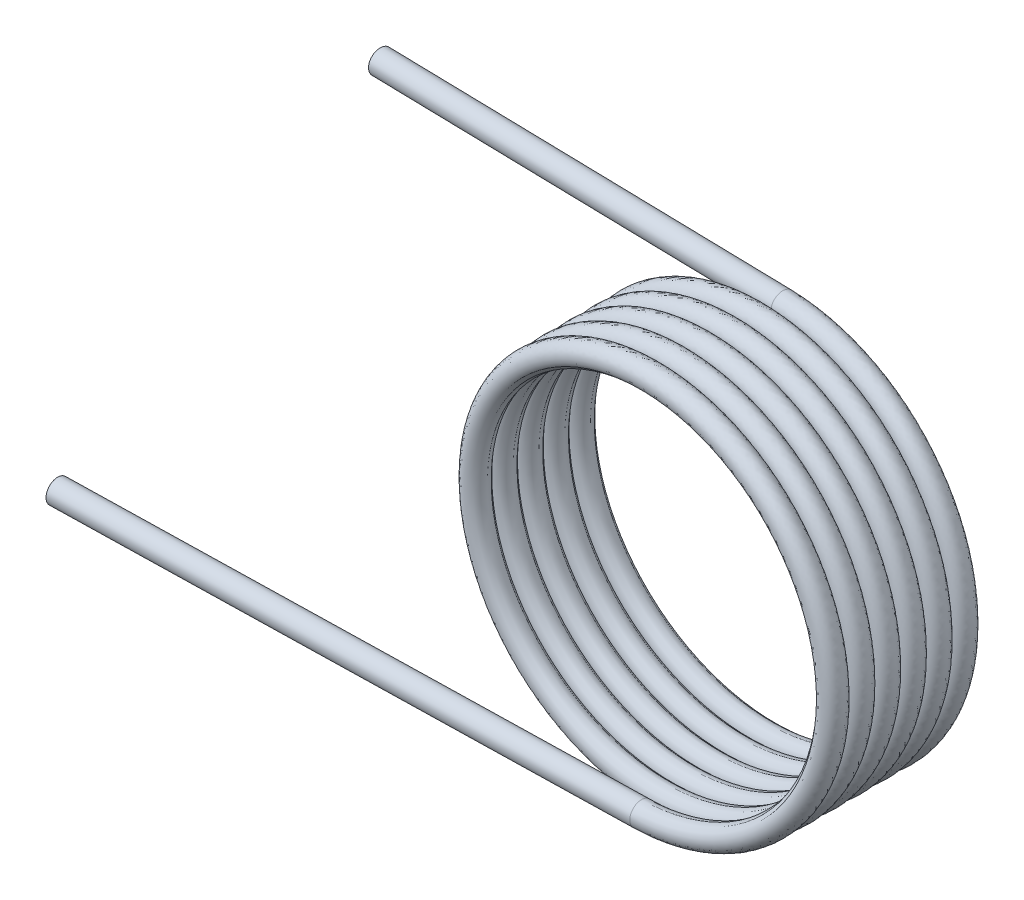
SolidWorks part; units mm, degrees
ref_plane "Front Plane" through (0, 0, 0) normal (0, 0, 1) x (1, 0, 0)
ref_plane "Top Plane" through (0, 0, 0) normal (0, 1, 0) x (1, 0, 0)
ref_plane "Right Plane" through (0, 0, 0) normal (1, 0, 0) x (0, 0, -1)
sketch "Sketch1" plane through (0, 0, 0) normal (0, 0, 1) x (1, 0, 0)
  circle A0 centre (0, 0) radius 23.19
  dimension "D1" = 46.38
curve "Helix/Spiral1" pitch 3.2291 height 17.76 turns 5.5
ref_plane "Plane1" through (0, -23.19, 17.76) normal (-0.9998, 0, 0.0222) x (0.0222, 0, 0.9998)
sketch "Sketch2" plane through (0, -23.19, 17.76) normal (-0.9998, 0, 0.0222) x (0.0222, 0, 0.9998)
  circle A1 centre (0, 0) radius 1.46
  dimension "D1" = 2.92
sweep "Sweep1" add profiles "Sketch2" path "Helix/Spiral1"
sketch "Sketch3" plane through (0, 0, 0) normal (-0.9998, 0, -0.0222) x (-0.0222, 0, 0.9998)
  circle A0 centre (0, 23.19) radius 1.46 construction
  circle A1 centre (0, 23.19) radius 1.46
extrude "Boss-Extrude1" add sketch "Sketch3" along normal blind 101.6
sketch "Sketch4" plane through (-0.3934, 0, 0.0087) normal (-0.9998, 0, 0.0222) x (0.0222, 0, 0.9998)
  circle A0 centre (17.7556, -23.19) radius 1.46 construction
  circle A1 centre (17.7556, -23.19) radius 1.46
extrude "Boss-Extrude2" add sketch "Sketch4" along normal blind 101.6
sketch "Sketch5" plane through (-101.5751, 0, -2.2511) normal (-0.9998, 0, -0.0222) x (-0.0222, 0, 0.9998)
  circle A0 centre (0, 23.19) radius 5.7146
extrude "Cut-Extrude1" cut sketch "Sketch5" against normal blind 50
sketch "Sketch6" plane through (-101.9685, 0, 2.2598) normal (-0.9998, 0, 0.0222) x (0.0222, 0, 0.9998)
  circle A0 centre (17.7556, -23.19) radius 6.6279
extrude "Cut-Extrude2" cut sketch "Sketch6" against normal blind 30
